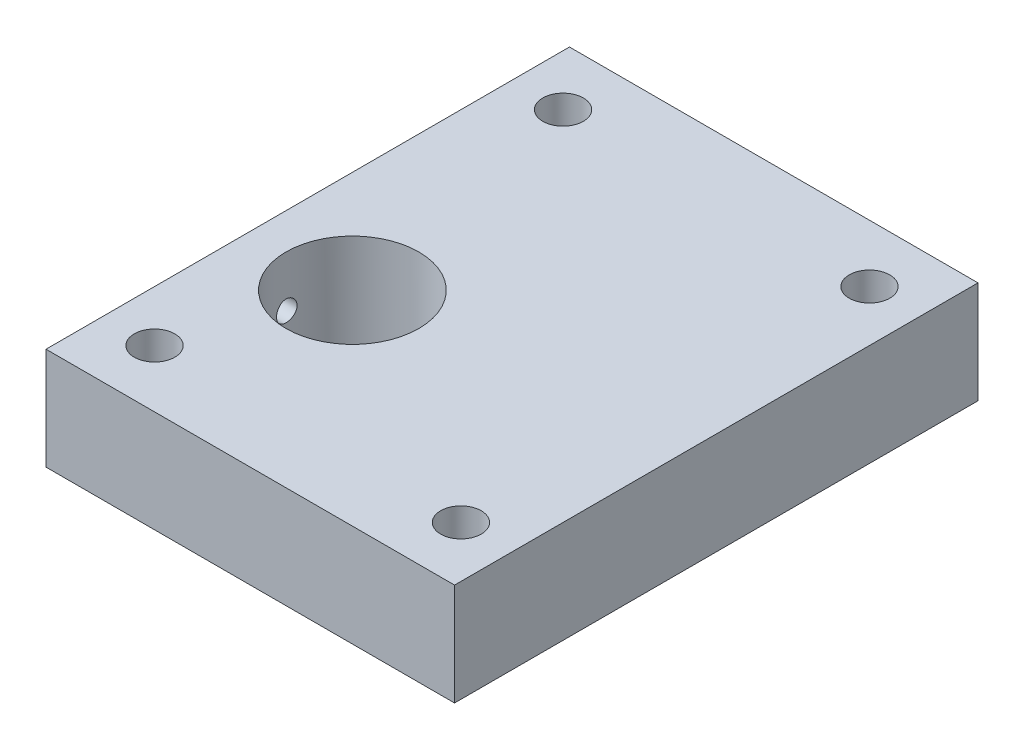
SolidWorks part; units mm, degrees
material "6061 Alloy"
ref_plane "Front" through (0, 0, 0) normal (0, 0, 1) x (1, 0, 0)
ref_plane "Top" through (0, 0, 0) normal (0, 1, 0) x (1, 0, 0)
ref_plane "Right" through (0, 0, 0) normal (1, 0, 0) x (0, 0, -1)
sketch "Sketch1" plane through (0, 0, 0) normal (0, 1, 0) x (1, 0, 0)
  line L1 (-50.8, -65.0875) -> (50.8, -65.0875)
  line L2 (-50.8, -65.0875) -> (-50.8, 65.0875)
  line L3 (-50.8, 65.0875) -> (50.8, 65.0875)
  line L4 (50.8, -65.0875) -> (50.8, 65.0875)
  line L5 (-50.8, -65.0875) -> (50.8, 65.0875) construction
  line L6 (-50.8, 65.0875) -> (50.8, -65.0875) construction
  point P0 (0, 0)
  dimension "D1" = 101.6
  dimension "D2" = 130.175
extrude "Boss-Extrude1" add sketch "Sketch1" along normal mid plane 25.4
sketch "Sketch2" plane through (0, 12.7, 0) normal (0, 1, 0) x (1, 0, 0)
  line L1 (-50.8, 65.0875) -> (-50.8, -65.0875) construction
  line L2 (-50.8, -65.0875) -> (50.8, -65.0875) construction
  circle A0 centre (-25.4, -14.2875) radius 16.51
  dimension "D2" = 33.02
  dimension "D1" = 25.4
  dimension "D3" = 50.8
extrude "Cut-Extrude1" cut sketch "Sketch2" against normal through all both and the other way through all
sketch "Sketch3" plane through (0, -12.7, 0) normal (0, -1, 0) x (1, 0, 0)
  point P0 (-38.1, 50.8)
  point P1 (38.1, 50.8)
  point P3 (38.1, -50.8)
  point P5 (-38.1, -50.8)
hole_wizard "3/8 Clearance Hole1" positions "Sketch4" profile "Sketch5" hole size "3/8" standard "ANSI Inch" end condition up to next
sketch "Sketch4" plane through (0, -12.7, 0) normal (0, -1, 0) x (-1, 0, 0)
  point P0 (-38.1, 50.8)
  point P3 (38.1, 50.8)
  point P6 (38.1, -50.8)
  point P9 (-38.1, -50.8)
sketch "Sketch5" plane through (38.1, -12.7, -50.8) normal (1, 0, 0) x (0, 0, -1)
  line L0 (0, 0) -> (0, 25.4)
  line L1 (0, 25.4) -> (5.0419, 25.4)
  line L2 (5.0419, 25.4) -> (5.0419, 0)
  line L5 (5.0419, 0) -> (0, 0)
  line L11 (0, -6.35) -> (0, 107.95) construction
  dimension "Thru Hole Dia." = 10.0838
  dimension "Thru Hole Depth" = 25.4
sketch "Sketch6" plane through (-50.8, 0, 0) normal (-1, 0, 0) x (0, 0, 1)
  line L0 (50, 0) -> (-50, 0) construction
  line L1 (65.0875, 12.7) -> (65.0875, -12.7) construction
  point P0 (14.2875, 0)
  dimension "D1" = 50.8
hole_wizard "1/4-20 Tapped Hole1" positions "Sketch7" profile "Sketch8" tap size "1/4-20" standard "ANSI Inch"
sketch "Sketch7" plane through (-50.8, 0, 0) normal (-1, 0, 0) x (0, 0, 1)
  point P0 (14.2875, 0)
sketch "Sketch8" plane through (-50.8, 0, 14.2875) normal (0, 1, 0) x (0, 0, 1)
  line L0 (0, 0) -> (0, 18.0438)
  line L1 (0, 18.0438) -> (2.5527, 16.51)
  line L2 (2.5527, 16.51) -> (2.5527, 0)
  line L5 (2.5527, 0) -> (0, 0)
  line L10 (0, 18.0438) -> (-2.5527, 16.51) construction
  line L11 (0, -6.35) -> (0, 107.95) construction
  dimension "Tap Drill Dia." = 5.1054
  dimension "Tap Drill Depth" = 16.51
  dimension "Drill Angle" = 118
cosmetic thread "Hole Thread1" parameters "D1"=12.7, "D2"=6.35
